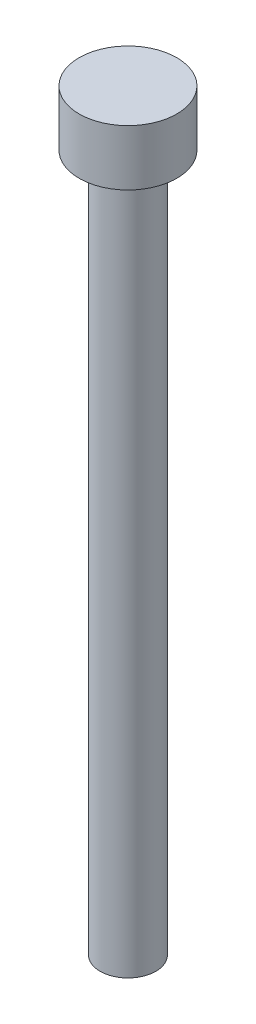
SolidWorks part; units mm, degrees
ref_plane "Front Plane" through (0, 0, 0) normal (0, 0, 1) x (1, 0, 0)
ref_plane "Top Plane" through (0, 0, 0) normal (0, 1, 0) x (1, 0, 0)
ref_plane "Right Plane" through (0, 0, 0) normal (1, 0, 0) x (0, 0, -1)
sketch "Sketch1" plane through (0, 0, 0) normal (0, 0, 1) x (1, 0, 0)
  line L0 (0, 54) -> (0, 0)
  line L1 (0, 54) -> (3.5, 54)
  line L2 (3.5, 54) -> (3.5, 50)
  line L3 (3.5, 50) -> (2, 50)
  line L4 (2, 50) -> (2, 0)
  line L5 (2, 0) -> (0, 0)
  dimension "D1" = 2
  dimension "D2" = 50
  dimension "D3" = 4
  dimension "D4" = 3.5
revolve "Revolve1" add sketch "Sketch1" angle 360 about L0
